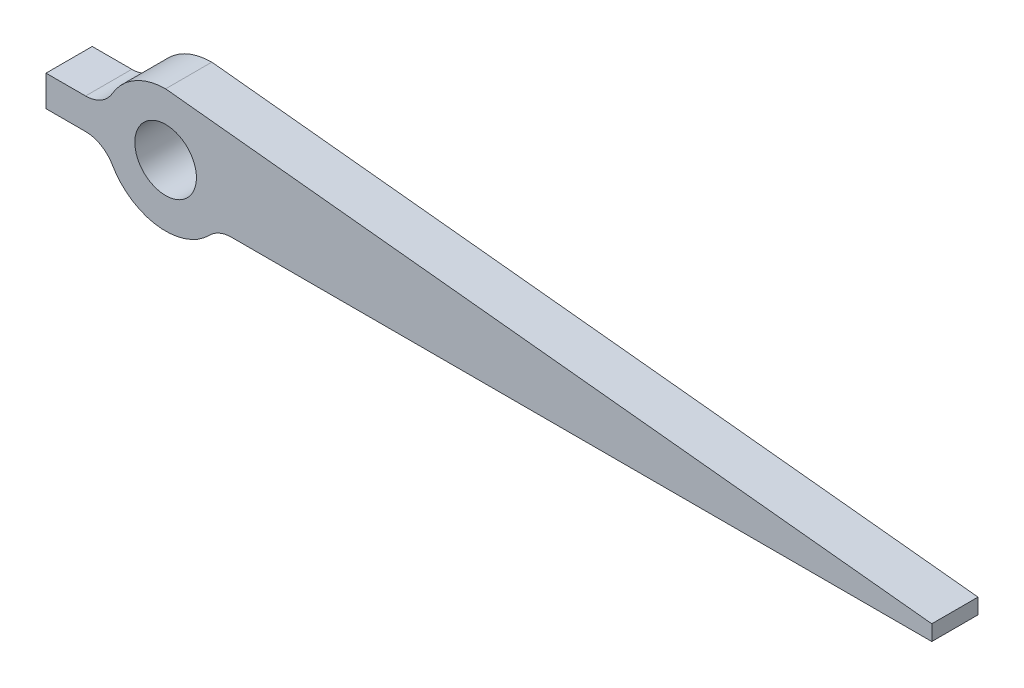
SolidWorks part; units mm, degrees
ref_plane "Front Plane" through (0, 0, 0) normal (0, 0, 1) x (1, 0, 0)
ref_plane "Top Plane" through (0, 0, 0) normal (0, 1, 0) x (1, 0, 0)
ref_plane "Right Plane" through (0, 0, 0) normal (1, 0, 0) x (0, 0, -1)
sketch "Sketch1" plane through (0, 0, 0) normal (0, 0, 1) x (1, 0, 0)
  line L6 (13.6481, 16.0477) -> (13.6481, 15.5477)
  line L11 (-10.8444, 15.7221) -> (-11.2161, 15.6505)
  line L12 (-11.2161, 18.6505) -> (13.6481, 16.0477)
  line L13 (-15.0981, 16.6505) -> (-15.0981, 17.1505)
  line L14 (-15.0981, 17.1505) -> (-13.1525, 17.1505)
  line L15 (-15.0981, 16.6505) -> (-15.0981, 16.1505)
  line L16 (-15.0981, 16.1505) -> (-13.1525, 16.1505)
  line L17 (-11.2161, 16.6505) -> (-11.2161, 16.1505)
  line L18 (13.6481, 15.5477) -> (-9.5476, 15.5477)
  circle A2 centre (-11.2161, 16.6505) radius 1
  circle A3 centre (-11.2161, 16.6505) radius 2
extrude "Boss-Extrude1" add sketch "Sketch1" along normal blind 1.5
fillet "Fillet1" radius 1 1 edges at (-13.1525, 16.1505, 0.75)
fillet "Fillet2" radius 1 1 edges at (-13.1525, 17.1505, 0.75)
fillet "Fillet3" radius 1 1 edges at (-9.5476, 15.5477, 0.75)
